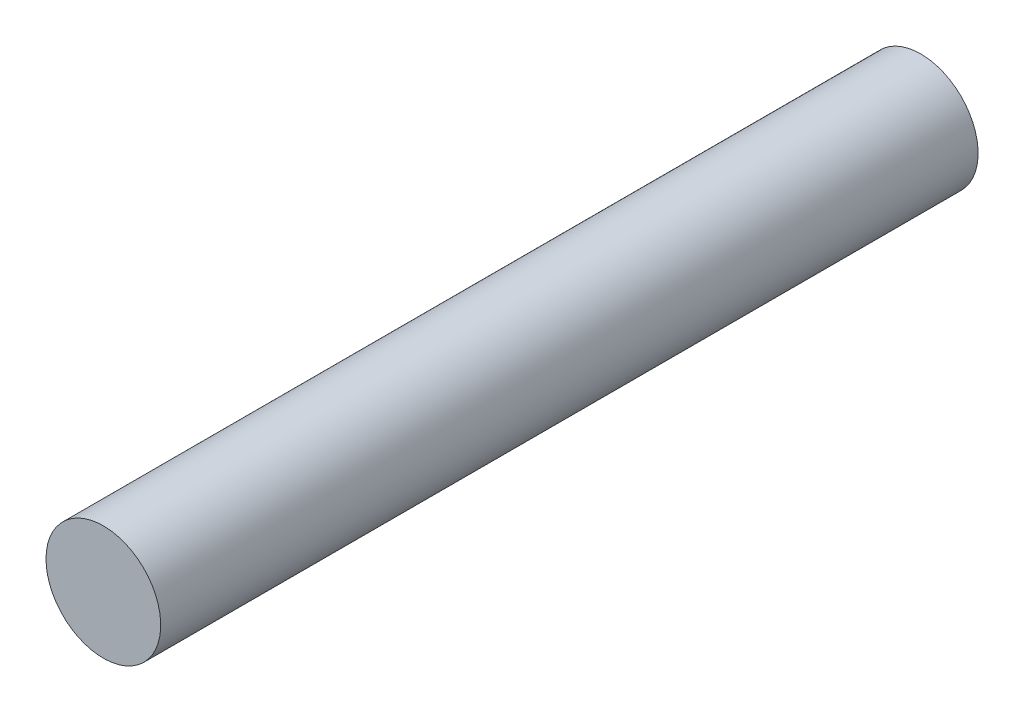
SolidWorks part; units mm, degrees
ref_plane "Спереди" through (0, 0, 0) normal (0, 0, 1) x (1, 0, 0)
ref_plane "Сверху" through (0, 0, 0) normal (0, 1, 0) x (1, 0, 0)
ref_plane "Справа" through (0, 0, 0) normal (1, 0, 0) x (0, 0, -1)
sketch "Эскиз1" plane through (0, 0, 0) normal (0, 0, 1) x (1, 0, 0)
  circle A0 centre (0, 0) radius 4
extrude "Вытянуть1" add sketch "Эскиз1" along normal blind 57
